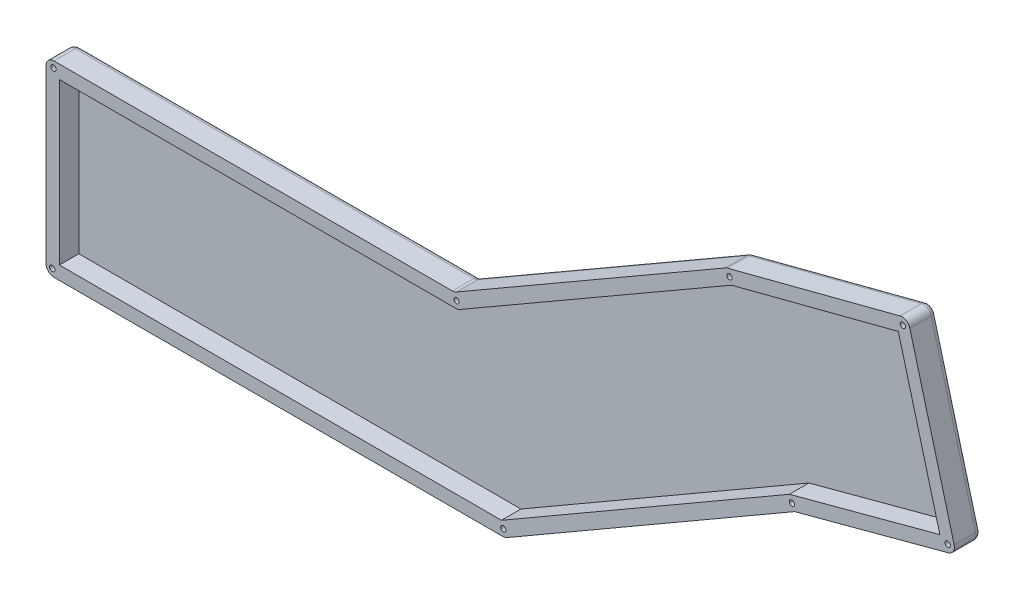
SolidWorks part; units mm, degrees
ref_plane "Plan de face" through (0, 0, 0) normal (0, 0, 1) x (1, 0, 0)
ref_plane "Plan de dessus" through (0, 0, 0) normal (0, 1, 0) x (1, 0, 0)
ref_plane "Plan de droite" through (0, 0, 0) normal (1, 0, 0) x (0, 0, -1)
sketch "Model" plane through (0, 0, 0) normal (0, 0, 1) x (1, 0, 0)
  line L0 (152.8114, 25.9717) -> (138.2826, 80.2215) construction
  line L1 (98.1506, 11.3316) -> (152.8114, 25.9717) construction
  line L2 (-9.3986, -50.8585) -> (98.1506, 11.3316) construction
  line L3 (-172.3739, -50.8585) -> (-9.3986, -50.8585) construction
  line L4 (-24.5886, 5.3017) -> (-172.3739, 5.2915) construction
  line L5 (138.2826, 80.2215) -> (78.0109, 64.5416) construction
  line L6 (-151.6088, 5.3124) -> (-151.6088, 5.2929)
  line L7 (-24.5886, 5.3017) -> (78.0109, 64.5416) construction
  line L8 (-172.3739, 5.2915) -> (-172.3739, -50.6876) construction
  line L9 (-172.3739, -50.6876) -> (-172.3739, -50.8585) construction
  line L10 (-25.1245, 7.3016) -> (-174.3739, 7.2914)
  line L11 (-174.3739, 7.2914) -> (-174.3739, -50.6876)
  line L12 (-174.3739, -50.6876) -> (-174.3739, -52.8585)
  line L13 (-174.3739, -52.8585) -> (-8.862, -52.8585)
  line L14 (-8.862, -52.8585) -> (98.9231, 9.4681)
  line L15 (98.9231, 9.4681) -> (155.2607, 24.5572)
  line L16 (155.2607, 24.5572) -> (139.7008, 82.657)
  line L17 (139.7008, 82.657) -> (77.2454, 66.409)
  line L18 (-25.1245, 7.3016) -> (77.2454, 66.409)
  line L19 (-26.4645, 12.3015) -> (-179.3739, 12.291)
  line L20 (-179.3739, 12.291) -> (-179.3739, -50.6876)
  line L21 (-179.3739, -50.6876) -> (-179.3739, -57.8585)
  line L22 (-179.3739, -57.8585) -> (-7.5204, -57.8585)
  line L23 (-7.5204, -57.8585) -> (100.8545, 4.8091)
  line L24 (100.8545, 4.8091) -> (161.3839, 21.021)
  line L25 (161.3839, 21.021) -> (143.2464, 88.7459)
  line L26 (143.2464, 88.7459) -> (75.3314, 71.0775)
  line L27 (-26.4645, 12.3015) -> (75.3314, 71.0775)
  circle A0 centre (80.6856, 58.4893) radius 1
  circle A1 centre (92.8776, 28.0855) radius 1
  circle A2 centre (-29.7028, -2.6485) radius 1
  circle A3 centre (-10.6528, -46.4381) radius 1
  circle A4 centre (-114.2594, -13.4181) radius 1
  circle A5 centre (-114.0308, -32.4935) radius 1
  dimension "D1" = 2
  dimension "D2" = 5
extrude "Boss.-Extru.1" add sketch "Model" along normal blind 10 contours L27 L19 L20 L21 L22 L23 L24 L25 L26 L10 L18 L17 L16 L15 L14 L13 L12 L11
fillet "Congé1" radius 3 8 edges at (-26.4645, 12.3015, 5) (75.3314, 71.0775, 5) (143.2464, 88.7459, 5) (161.3839, 21.021, 5) (100.8545, 4.8091, 5) (-7.5204, -57.8585, 5) (-179.3739, -57.8585, 5) (-179.3739, 12.291, 5)
sketch "Esquisse1" plane through (0, 0, 0) normal (0, 0, 1) x (1, 0, 0)
  line L0 (-25.1245, 7.3016) -> (-174.3739, 7.2914) construction
  line L1 (-25.1245, 7.3016) -> (77.2454, 66.409) construction
  line L2 (139.7008, 82.657) -> (77.2454, 66.409) construction
  line L3 (155.2607, 24.5572) -> (139.7008, 82.657) construction
  line L4 (98.9231, 9.4681) -> (155.2607, 24.5572) construction
  line L5 (-8.862, -52.8585) -> (98.9231, 9.4681) construction
  line L6 (-174.3739, -52.8585) -> (-8.862, -52.8585) construction
  line L7 (-174.3739, -50.6876) -> (-174.3739, -52.8585) construction
  line L8 (-174.3739, 7.2914) -> (-174.3739, -50.6876) construction
  line L9 (-25.1245, 7.3016) -> (-174.3739, 7.2914)
  line L10 (-25.1245, 7.3016) -> (77.2454, 66.409)
  line L11 (139.7008, 82.657) -> (77.2454, 66.409)
  line L12 (155.2607, 24.5572) -> (139.7008, 82.657)
  line L13 (98.9231, 9.4681) -> (155.2607, 24.5572)
  line L14 (-8.862, -52.8585) -> (98.9231, 9.4681)
  line L15 (-174.3739, -52.8585) -> (-8.862, -52.8585)
  line L16 (-174.3739, -50.6876) -> (-174.3739, -52.8585)
  line L17 (-174.3739, 7.2914) -> (-174.3739, -50.6876)
extrude "Boss.-Extru.2" add sketch "Esquisse1" along normal blind 2.7
sketch "Esquisse3" plane through (0, 0, 0) normal (0, 0, 1) x (1, 0, 0)
  circle A0 centre (158.2016, 22.9581) radius 1
  circle A1 centre (141.3885, 85.5343) radius 1
  circle A2 centre (76.5002, 68.7766) radius 1
  circle A3 centre (99.8904, 7.0714) radius 1
  circle A4 centre (-8.1724, -55.2759) radius 1
  circle A5 centre (-25.6914, 9.9201) radius 1
  circle A6 centre (-176.5621, 9.9201) radius 1
  circle A7 centre (-177.0296, -55.2759) radius 1
sketch "Esquisse2" plane through (0, 0, 0) normal (0, 0, -1) x (-1, 0, 0)
  circle A0 centre (-80.6856, 58.4893) radius 1 construction
  circle A1 centre (-92.8776, 28.0855) radius 1 construction
  circle A2 centre (29.7028, -2.6485) radius 1 construction
  circle A3 centre (10.6528, -46.4381) radius 1 construction
  circle A4 centre (114.2594, -13.4181) radius 1 construction
  circle A5 centre (114.0308, -32.4935) radius 1 construction
  circle A6 centre (-80.6856, 58.4893) radius 1
  circle A7 centre (-92.8776, 28.0855) radius 1
  circle A8 centre (29.7028, -2.6485) radius 1
  circle A9 centre (10.6528, -46.4381) radius 1
  circle A10 centre (114.2594, -13.4181) radius 1
  circle A11 centre (114.0308, -32.4935) radius 1
  circle A12 centre (-80.6856, 58.4893) radius 2
  circle A13 centre (-92.8776, 28.0855) radius 2
  circle A14 centre (29.7028, -2.6485) radius 2
  circle A15 centre (10.6528, -46.4381) radius 2
  circle A16 centre (114.2594, -13.4181) radius 2
  circle A17 centre (114.0308, -32.4935) radius 2
  dimension "D1" = 1
fillet "Congé2" radius 2 16 edges at (100.8645, 4.785, 0) (46.844, -26.4224, 0) (-7.5479, -57.756, 0) (-92.3496, -57.8585, 0) (-178.4952, -56.9798, 0) (-179.3739, -22.7836, 0) (-178.4953, 11.4125, 0) (-101.8212, 12.2964, 0) (-26.4919, 12.4038, 0) (24.6056, 41.7889, 0) (75.3418, 71.0522, 0) (108.0441, 79.5878, 0) (142.6286, 87.6851, 0) (152.3124, 54.8937, 0) (160.3079, 21.6424, 0) (129.8616, 12.5782, 0)
extrude "Enlèv. mat.-Extru.1" cut sketch "Esquisse3" along normal blind 20
sketch "Esquisse4" plane through (0, 0, 0) normal (0, 0, -1) x (-1, 0, 0)
  circle A0 centre (177.0296, -55.2759) radius 2
  circle A1 centre (176.5621, 9.9201) radius 2
  circle A2 centre (25.6914, 9.9201) radius 2
  circle A3 centre (-76.5002, 68.7766) radius 2
  circle A4 centre (-141.3885, 85.5343) radius 2
  circle A5 centre (-158.2016, 22.9581) radius 2
  circle A6 centre (-99.8904, 7.0714) radius 2
  circle A7 centre (8.1724, -55.2759) radius 2
extrude "Enlèv. mat.-Extru.2" cut sketch "Esquisse4" against normal blind 2
